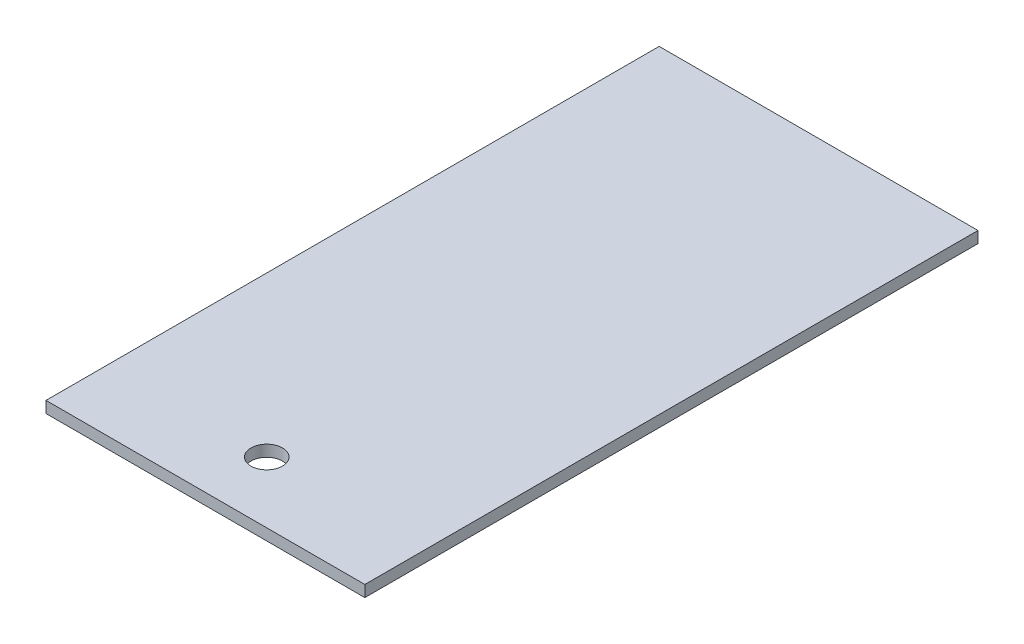
SolidWorks part; units mm, degrees
ref_plane "Front Plane" through (0, 0, 0) normal (0, 0, 1) x (1, 0, 0)
ref_plane "Top Plane" through (0, 0, 0) normal (0, 1, 0) x (1, 0, 0)
ref_plane "Right Plane" through (0, 0, 0) normal (1, 0, 0) x (0, 0, -1)
sketch "Sketch1" plane through (0, 0, 0) normal (0, 1, 0) x (1, 0, 0)
  line L1 (0, 0) -> (66.04, 0)
  line L2 (0, 0) -> (0, 127)
  line L3 (0, 127) -> (66.04, 127)
  line L4 (66.04, 0) -> (66.04, 127)
  dimension "D1" = 66.04
  dimension "D2" = 127
extrude "Boss-Extrude1" add sketch "Sketch1" along normal blind 2.3622
sketch "Sketch2" plane through (0, 2.3622, 0) normal (0, 1, 0) x (1, 0, 0)
  line L0 (0, 0) -> (66.04, 0) construction
  circle A0 centre (33.02, 12.7) radius 3.2639
  point P2 (33.02, 0)
  point P3 (25.3831, 12.7)
  point P6 (0, 0)
  dimension "D1" = 6.5278
  dimension "D2" = 12.7
extrude "Cut-Extrude1" cut sketch "Sketch2" against normal through all
